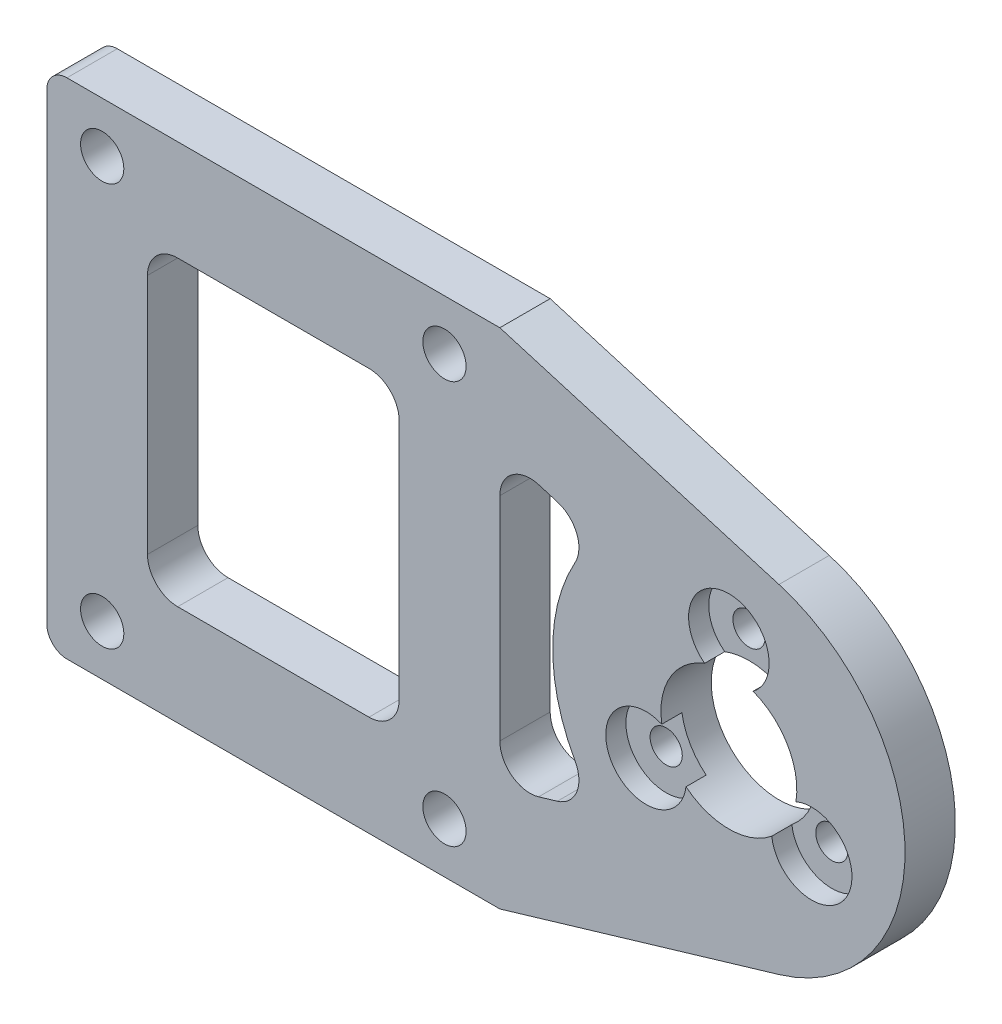
SolidWorks part; units mm, degrees
material "5052-H34"
ref_plane "正面" through (0, 0, 0) normal (0, 0, 1) x (1, 0, 0)
ref_plane "平面" through (0, 0, 0) normal (0, 1, 0) x (1, 0, 0)
ref_plane "右側面" through (0, 0, 0) normal (1, 0, 0) x (0, 0, -1)
sketch "ｽｹｯﾁ1" plane through (0, 0, 0) normal (0, 0, 1) x (1, 0, 0)
  line L0 (22.5, 50) -> (22.5, 0) construction
  line L1 (0, 0) -> (45, 0)
  line L2 (0, 0) -> (0, 50)
  line L3 (0, 50) -> (45, 50)
  line L4 (45, 0) -> (45, 50)
  line L5 (45, 25) -> (0, 25) construction
  line L6 (67.75, 25) -> (67.75, 34.5) construction
  line L7 (10, 10) -> (35, 10)
  line L8 (10, 10) -> (10, 40)
  line L9 (10, 40) -> (35, 40)
  line L10 (35, 10) -> (35, 40)
  line L11 (10, 10) -> (35, 40) construction
  line L12 (10, 40) -> (35, 10) construction
  line L13 (49.75, 50) -> (49.75, 0) construction
  line L14 (45, 50) -> (72.7256, 41.7778)
  line L15 (45, 0) -> (72.7256, 8.2222)
  line L16 (45, 39.5695) -> (54.7235, 36.6859)
  line L17 (42.1568, 40.4127) -> (69.8824, 32.1905) construction
  line L18 (45, 10.4305) -> (54.7235, 13.3141)
  circle A0 centre (5.5, 5) radius 2.15
  circle A1 centre (5.5, 45) radius 2.15
  circle A2 centre (39.5, 5) radius 2.15
  circle A3 centre (39.5, 45) radius 2.15
  circle A4 centre (67.75, 25) radius 6.75
  circle A5 centre (67.75, 34.5) radius 1.6
  circle A6 centre (75.9772, 20.25) radius 1.6
  circle A7 centre (59.5228, 20.25) radius 1.6
  circle A8 centre (67.75, 25) radius 17.5
  circle A9 centre (67.75, 25) radius 18 construction
  point P17 (22.5, 25)
  point P32 (67.75, 25)
  dimension "D3" = 5.5
  dimension "D4" = 5
  dimension "D5" = 4.3
  dimension "D8" = 13.5
  dimension "D10" = 3.2
  dimension "D13" = 36
  dimension "D14" = 35
  dimension "D1" = 45
  dimension "D2" = 50
  dimension "D6" = 25
  dimension "D7" = 10
  dimension "D9" = 9.5
  dimension "D12" = 49.75
  dimension "D15" = 10
  dimension "D11" = 3
extrude "ﾎﾞｽ - 押し出し1" add sketch "ｽｹｯﾁ1" along normal blind 5 contours L1 L4 L3 L2 A3 A1 A0 L10 L7 L8 L9 A2 | A8 A4 A5 A6 A7 | A8 L14 L4 L16 | A8 L18 L4 L15
sketch "ｽｹｯﾁ2" plane through (0, 0, 5) normal (0, 0, 1) x (1, 0, 0)
  circle A0 centre (67.75, 34.5) radius 4
  circle A1 centre (67.75, 25) radius 6.75 construction
  circle A2 centre (67.75, 25) radius 6.75
  circle A3 centre (75.9772, 20.25) radius 4
  circle A4 centre (59.5228, 20.25) radius 4
  point P14 (67.75, 25)
  circle M35 centre (67.75, 25) radius 6.75
  circle M36 centre (67.75, 34.5) radius 1.6
  circle M37 centre (75.9772, 20.25) radius 1.6
  circle M38 centre (59.5228, 20.25) radius 1.6
  dimension "D1" = 8
  dimension "D2" = 3
extrude "ｶｯﾄ - 押し出し1" cut sketch "ｽｹｯﾁ2" against normal blind 2 contours A0 M35 M36 | A2 A4 M38 | A2 A3 M37
fillet "ﾌｨﾚｯﾄ2" radius 3 8 edges at (10, 10, 2.5) (35, 10, 2.5) (35, 40, 2.5) (10, 40, 2.5) (54.7235, 36.6859, 2.5) (54.7235, 13.3141, 2.5) (45, 10.4305, 2.5) (45, 39.5695, 2.5)
fillet "ﾌｨﾚｯﾄ3" radius 2 2 edges at (0, 0, 2.5) (0, 50, 2.5)
